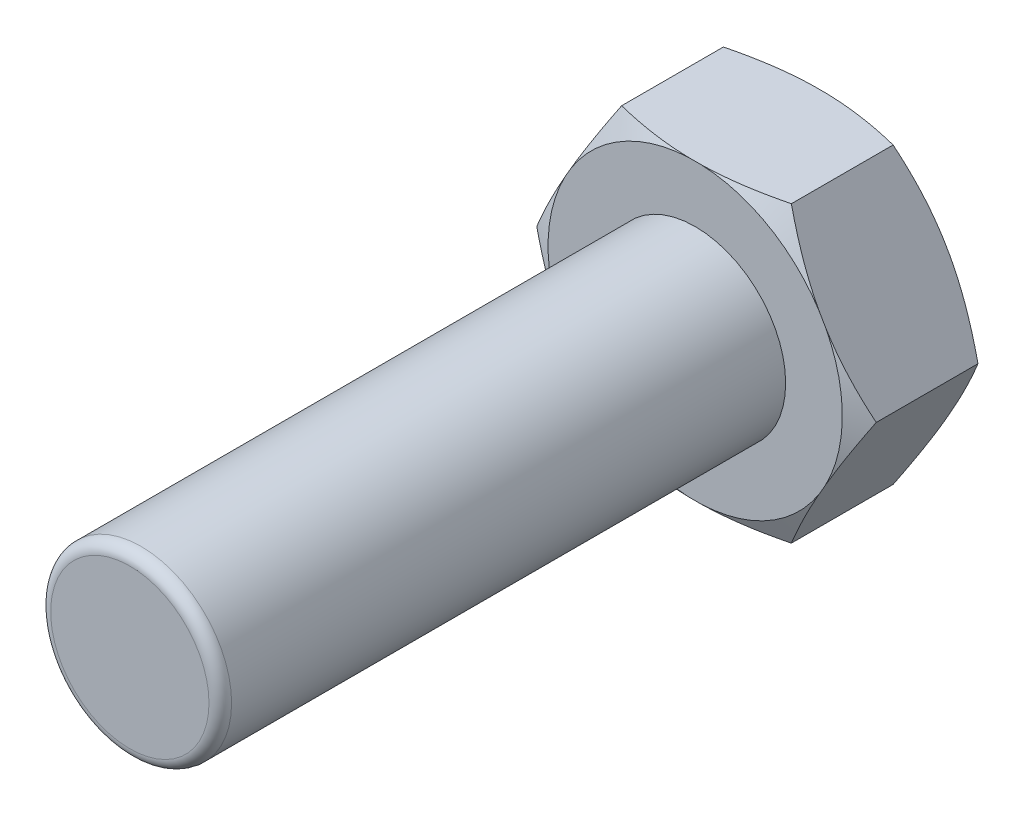
SolidWorks part; units mm, degrees
material "1.0036 (S235JRG1)"
ref_plane "Ön Düzlem" through (0, 0, 0) normal (0, 0, 1) x (1, 0, 0)
ref_plane "Üst Düzlem" through (0, 0, 0) normal (0, 1, 0) x (1, 0, 0)
ref_plane "Sağ Düzlem" through (0, 0, 0) normal (1, 0, 0) x (0, 0, -1)
sketch "Çizim1" plane through (0, 0, 0) normal (0, 0, 1) x (1, 0, 0)
  line L1 (7.5056, 0) -> (3.7528, 6.5)
  line L2 (3.7528, 6.5) -> (-3.7528, 6.5)
  line L3 (-3.7528, 6.5) -> (-7.5056, 0)
  line L4 (-7.5056, 0) -> (-3.7528, -6.5)
  line L5 (-3.7528, -6.5) -> (3.7528, -6.5)
  line L6 (3.7528, -6.5) -> (7.5056, 0)
  circle A0 centre (0, 0) radius 6.5 construction
  dimension "D1" = 13
extrude "Yükseklik-Ekstrüzyon1" add sketch "Çizim1" along normal blind 5.5
sketch "Çizim2" plane through (0, 0, 5.5) normal (0, 0, 1) x (1, 0, 0)
  circle A0 centre (0, 0) radius 4
  dimension "D1" = 8
extrude "Yükseklik-Ekstrüzyon2" add sketch "Çizim2" along normal blind 25
cosmetic thread "Kozmetik Diş Açma1" parameters "D2"=6.619
sketch "Çizim3" plane through (0, 0, 0) normal (0, 1, 0) x (1, 0, 0)
  line L0 (-7.5056, 0) -> (-6.5056, 0)
  line L1 (-3.7528, 0) -> (-7.5056, 0) construction
  line L2 (-6.5056, 0) -> (-7.5056, -0.5)
  line L3 (-7.5056, -5.5) -> (-7.5056, 0) construction
  line L4 (-7.5056, -0.5) -> (-7.5056, 0)
  line L9 (-7.5056, -5.5) -> (-7.5056, -5)
  line L10 (-7.5056, -5) -> (-6.5056, -5.5)
  line L11 (-3.7528, -5.5) -> (-7.5056, -5.5) construction
  line L12 (-6.5056, -5.5) -> (-7.5056, -5.5)
  line L13 (0, 0) -> (0, -5.5) construction
  line L14 (-4, -5.5) -> (4, -5.5) construction
  dimension "D1" = 1
  dimension "D2" = 0.5
  dimension "D3" = 0.5
  dimension "D4" = 1
revolve "Kes-Döndür1" cut sketch "Çizim3" angle 360 about L13
fillet "Radyus1" radius 0.5 1 edges at (4, 0, 30.5)
